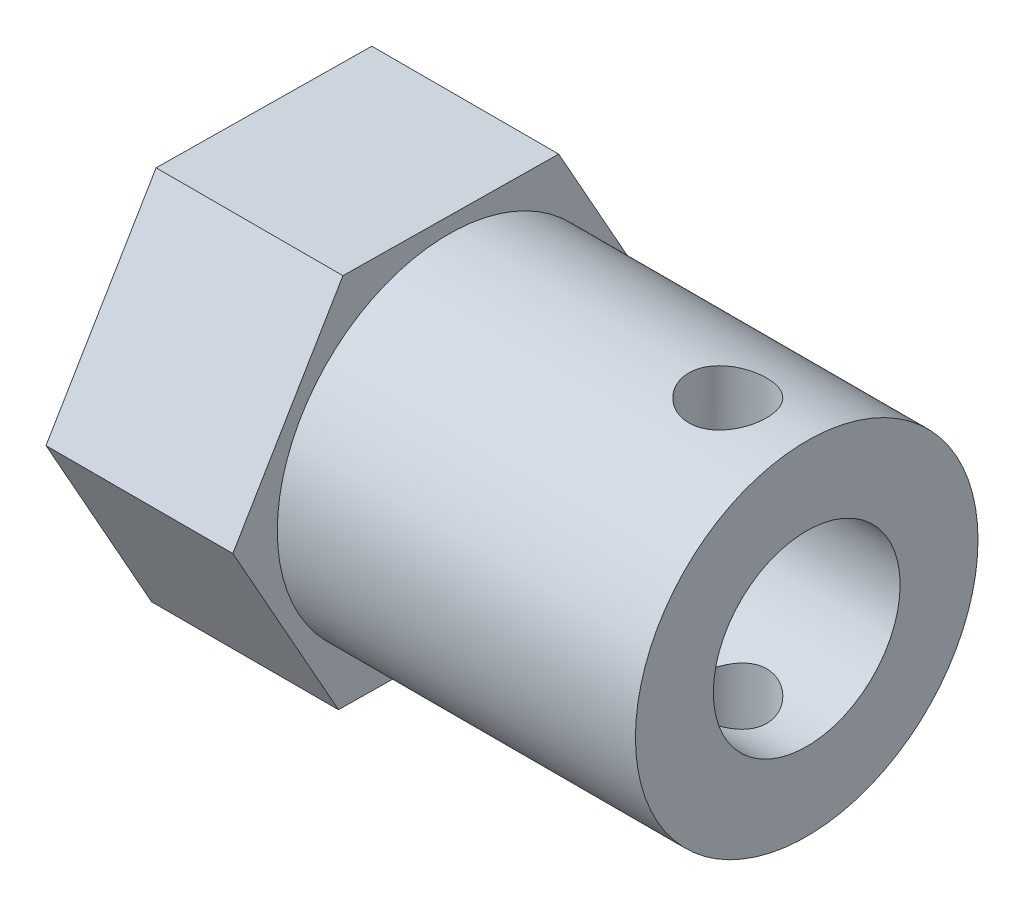
SolidWorks part; units mm, degrees
ref_plane "Front Plane" through (0, 0, 0) normal (0, 0, 1) x (1, 0, 0)
ref_plane "Top Plane" through (0, 0, 0) normal (0, 1, 0) x (1, 0, 0)
ref_plane "Right Plane" through (0, 0, 0) normal (1, 0, 0) x (0, 0, -1)
sketch "Sketch1" plane through (0, 0, 0) normal (1, 0, 0) x (0, 0, -1)
  circle A0 centre (0, 0) radius 5.5
  dimension "D1" = 11
extrude "Boss-Extrude1" add sketch "Sketch1" along normal blind 11.5
sketch "Sketch2" plane through (0, 0, 0) normal (-1, 0, 0) x (0, 0, 1)
  line L2 (3.3923, 6.0409) -> (-3.5354, 5.9583)
  line L3 (-3.5354, 5.9583) -> (-6.9277, -0.0826)
  line L4 (-6.9277, -0.0826) -> (-3.3923, -6.0409)
  line L5 (-3.3923, -6.0409) -> (3.5354, -5.9583)
  line L6 (3.5354, -5.9583) -> (6.9277, 0.0826)
  line L7 (6.9277, 0.0826) -> (3.3923, 6.0409)
  circle A0 centre (0, 0) radius 6 construction
  dimension "D2" = 12
extrude "Boss-Extrude2" add sketch "Sketch2" along normal blind 6
sketch "Sketch3" plane through (11.5, 0, 0) normal (1, 0, 0) x (0, 0, -1)
  circle A0 centre (0, 0) radius 3
  dimension "D1" = 6
extrude "Cut-Extrude1" cut sketch "Sketch3" against normal blind 10
sketch "Sketch4" plane through (0, 0, 0) normal (0, 1, 0) x (1, 0, 0)
  circle A0 centre (8.9654, 0) radius 1.25
  dimension "D2" = 2.5
extrude "Cut-Extrude4" cut sketch "Sketch4" against normal mid plane 20
sketch "Sketch5" plane through (-6, 0, 0) normal (-1, 0, 0) x (0, 0, 1)
  circle A0 centre (0, 0) radius 1.5
  dimension "D1" = 3
extrude "Cut-Extrude5" cut sketch "Sketch5" against normal blind 5
